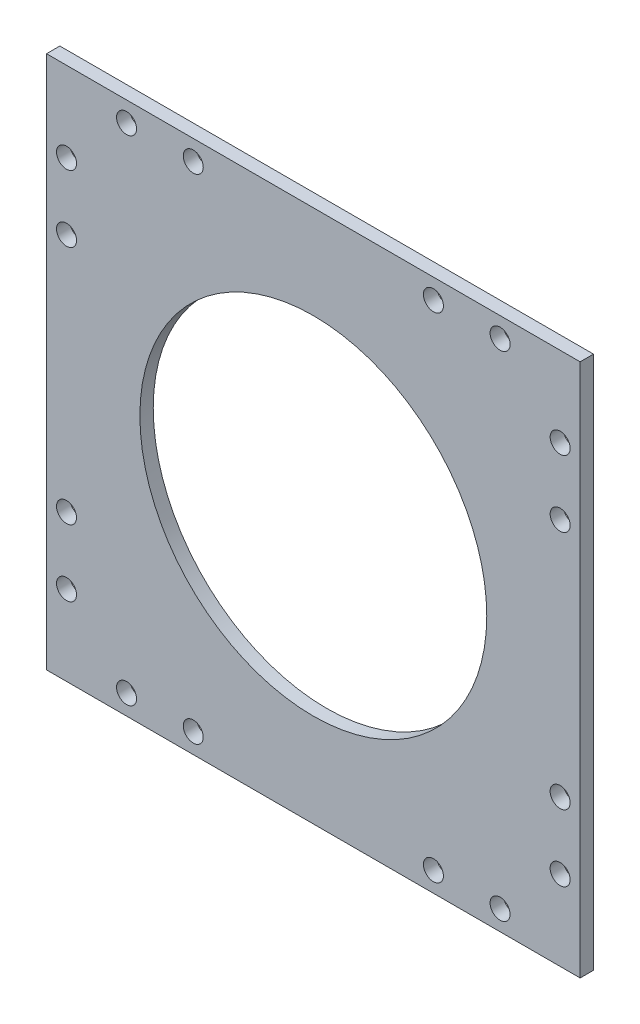
SolidWorks part; units mm, degrees
material "Thornel Mat VMA"
ref_plane "前视基准面" through (0, 0, 0) normal (0, 0, 1) x (1, 0, 0)
ref_plane "上视基准面" through (0, 0, 0) normal (0, 1, 0) x (1, 0, 0)
ref_plane "右视基准面" through (0, 0, 0) normal (1, 0, 0) x (0, 0, -1)
other "Configuration Table"
sketch "草图1" plane through (0, 0, 0) normal (0, 0, 1) x (1, 0, 0)
  line L1 (-40, 40) -> (40, 40)
  line L2 (-40, 40) -> (-40, -40)
  line L3 (-40, -40) -> (40, -40)
  line L4 (40, 40) -> (40, -40)
  line L5 (-40, 40) -> (40, -40) construction
  line L6 (-40, -40) -> (40, 40) construction
  circle A0 centre (0, 0) radius 26
  point P0 (0, 0)
  dimension "D3" = 52
  dimension "D1" = 80
  dimension "D2" = 80
extrude "凸台-拉伸1" add sketch "草图1" along normal blind 2
sketch "草图2" plane through (0, 0, 2) normal (0, 0, 1) x (1, 0, 0)
  line L0 (40, 40) -> (-40, 40) construction
  line L1 (-40, -40) -> (40, -40) construction
  line L2 (40, -40) -> (40, 40) construction
  line L3 (0, 0) -> (0, -7.4308) construction
  line L4 (-40, 40) -> (-40, -40) construction
  line L5 (0, 0) -> (-6.8349, 0) construction
  circle A0 centre (37, 28) radius 1.5
  circle A1 centre (37, 18) radius 1.5
  circle A2 centre (37, -18) radius 1.5
  circle A3 centre (37, -28) radius 1.5
  circle A4 centre (-37, -28) radius 1.5
  circle A5 centre (-37, -18) radius 1.5
  circle A6 centre (-37, 18) radius 1.5
  circle A7 centre (-37, 28) radius 1.5
  circle A8 centre (-28, 37) radius 1.5
  circle A9 centre (-18, 37) radius 1.5
  circle A10 centre (18, 37) radius 1.5
  circle A11 centre (28, 37) radius 1.5
  circle A12 centre (28, -37) radius 1.5
  circle A13 centre (18, -37) radius 1.5
  circle A14 centre (-18, -37) radius 1.5
  circle A15 centre (-28, -37) radius 1.5
  dimension "D1" = 10
  dimension "D2" = 10
  dimension "D3" = 12
  dimension "D4" = 12
  dimension "D5" = 3
  dimension "D6" = 3
  dimension "D7" = 10
  dimension "D8" = 10
  dimension "D9" = 12
  dimension "D11" = 3
  dimension "D12" = 3
  dimension "D13" = 3
  dimension "D14" = 3
  dimension "D15" = 3
  dimension "D16" = 3
  dimension "D17" = 3
  dimension "D10" = 12
extrude "切除-拉伸1" cut sketch "草图2" against normal through all
sketch "草图3" plane through (0, 0, 2) normal (0, 0, 1) x (1, 0, 0)
  line L4 (40, -40) -> (40, 40)
  line L5 (40, 40) -> (-40, 40)
  line L6 (-40, 40) -> (-40, -40)
  line L7 (-40, -40) -> (40, -40)
  line L8 (40, -40) -> (40, 40)
  line L9 (40, 40) -> (-40, 40)
  line L10 (-40, 40) -> (-40, -40)
  line L11 (-40, -40) -> (40, -40)
  circle A0 centre (-37, 18) radius 1.5 construction
  circle A1 centre (-37, 18) radius 1.5
  circle A3 centre (18, 37) radius 1.5
  circle A4 centre (18, 37) radius 1.5
  circle A5 centre (28, 37) radius 1.5
  circle A6 centre (28, 37) radius 1.5
  circle A7 centre (37, 28) radius 1.5
  circle A8 centre (37, 28) radius 1.5
  circle A9 centre (37, 18) radius 1.5
  circle A10 centre (37, 18) radius 1.5
  circle A11 centre (37, -18) radius 1.5
  circle A12 centre (37, -18) radius 1.5
  circle A13 centre (37, -28) radius 1.5
  circle A14 centre (37, -28) radius 1.5
  circle A15 centre (28, -37) radius 1.5
  circle A16 centre (28, -37) radius 1.5
  circle A17 centre (18, -37) radius 1.5
  circle A18 centre (18, -37) radius 1.5
  circle A19 centre (-18, -37) radius 1.5
  circle A20 centre (-18, -37) radius 1.5
  circle A21 centre (-28, -37) radius 1.5
  circle A22 centre (-28, -37) radius 1.5
  circle A23 centre (-37, -28) radius 1.5
  circle A24 centre (-37, -28) radius 1.5
  circle A25 centre (-37, -18) radius 1.5
  circle A26 centre (-37, -18) radius 1.5
  circle A27 centre (-18, 37) radius 1.5
  circle A28 centre (-18, 37) radius 1.5
  circle A29 centre (-28, 37) radius 1.5
  circle A30 centre (-28, 37) radius 1.5
  circle A31 centre (-37, 28) radius 1.5
  circle A32 centre (-37, 28) radius 1.5
  dimension "D1" = 0
  dimension "D2" = 0
  dimension "D3" = 0
  dimension "D4" = 0
  dimension "D5" = 0
  dimension "D6" = 0
  dimension "D7" = 0
  dimension "D8" = 0
  dimension "D9" = 0
  dimension "D10" = 0
  dimension "D11" = 0
  dimension "D12" = 0
  dimension "D13" = 0
  dimension "D14" = 0
  dimension "D15" = 0
  dimension "D16" = 0
